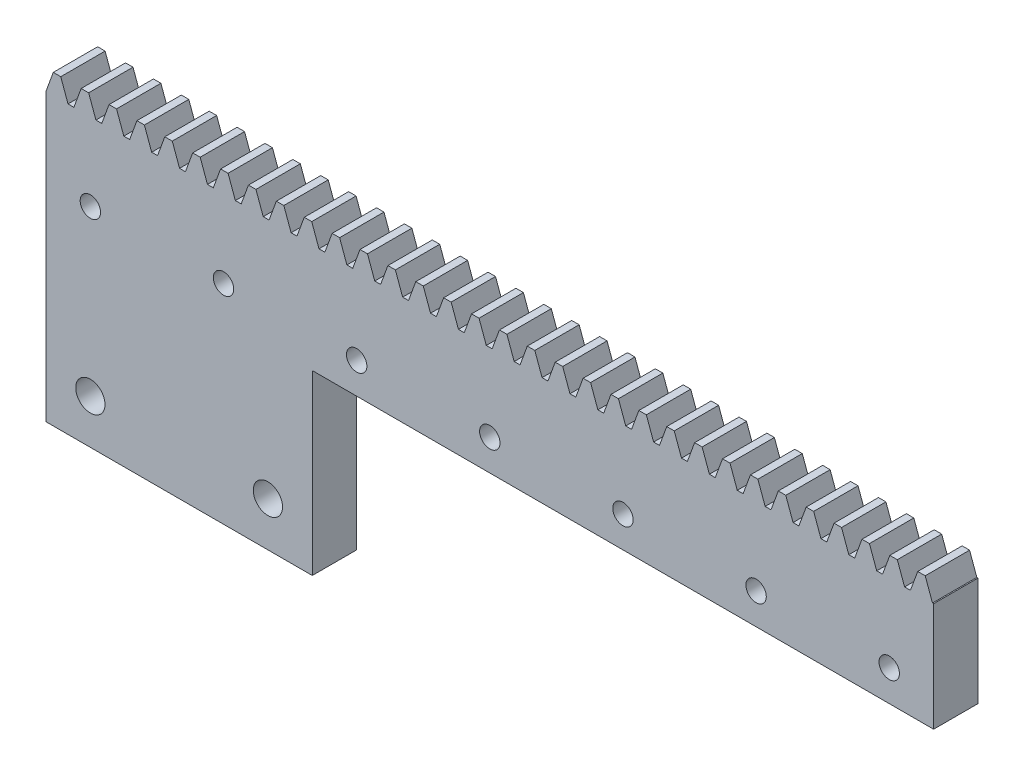
SolidWorks part; units mm, degrees
material "1.1193 (C45G)"
ref_plane "Front" through (0, 0, 0) normal (0, 0, 1) x (1, 0, 0)
ref_plane "Top" through (0, 0, 0) normal (0, 1, 0) x (1, 0, 0)
ref_plane "Right" through (0, 0, 0) normal (1, 0, 0) x (0, 0, -1)
sketch "Sketch1" plane through (0, 0, 0) normal (0, 0, 1) x (1, 0, 0)
  line L1 (0, 0) -> (106.8142, 0)
  line L2 (0, 0) -> (0, -8)
  line L3 (0, -8) -> (106.8142, -8)
  line L4 (106.8142, 0) -> (106.8142, -8)
  dimension "D1" = 8
  dimension "L" = 106.8142
extrude "Extrude1" add sketch "Sketch1" along normal blind 5
sketch "Sketch2" plane through (0, 0, 5) normal (0, 0, 1) x (1, 0, 0)
  line L0 (0, 0) -> (0.8189, 2.25)
  line L1 (0.8189, 2.25) -> (1.6618, 2.25)
  line L2 (1.6618, 2.25) -> (2.4807, 0)
  line L3 (106.8142, 0) -> (0, 0) construction
  line L4 (0, 0) -> (2.4807, 0)
  line L5 (0.455, 1.25) -> (2.0258, 1.25) construction
  dimension "alpha2" = 70
  dimension "alpha" = 110
  dimension "ha" = 1
  dimension "hf" = 1.25
  dimension "S" = 1.5708
extrude "Extrude2" add sketch "Sketch2" against normal up to surface (5 mm away) up to face at (53.4071, -4, 0)
pattern_linear "LPattern1" count 34 spacing 3.1416 along (1, 0, 0) of "Extrude2"
sketch "草图1" plane through (0, 0, 5) normal (0, 0, 1) x (1, 0, 0)
  line L0 (-1.6813, 1.25) -> (108.7223, 1.25) construction
  line L1 (3.1416, 0) -> (2.4807, 0) construction
  dimension "D1" = 1.25
sketch "草图2" plane through (0, -8, 0) normal (0, -1, 0) x (1, 0, 0)
  line L4 (0, 0) -> (106.8142, 0)
  line L5 (106.8142, 0) -> (106.8142, 5)
  line L6 (106.8142, 5) -> (0, 5)
  line L7 (0, 5) -> (0, 0)
  line L8 (0, 0) -> (106.8142, 0)
  line L9 (106.8142, 0) -> (106.8142, 5)
  line L10 (106.8142, 5) -> (0, 5)
  line L11 (0, 5) -> (0, 0)
  dimension "D1" = 0
extrude "凸台-拉伸1" add sketch "草图2" along normal blind 4.25
sketch "草图3" plane through (106.8142, 0, 0) normal (1, 0, 0) x (0, 0, -1)
  line L1 (-5, -12.25) -> (0, -12.25)
  line L2 (-5, -12.25) -> (-5, 5.5099)
  line L3 (-5, 5.5099) -> (0, 5.5099)
  line L4 (0, -12.25) -> (0, 5.5099)
extrude "切除-拉伸1" cut sketch "草图3" against normal offset from surface (6.8142 mm away) 100 up to face at (0, -6.125, 2.5)
sketch "草图4" plane through (0, 0, 5) normal (0, 0, 1) x (1, 0, 0)
  line L0 (0, -8.75) -> (100, -8.75) construction
  line L1 (0, 0) -> (0, -12.25) construction
  line L2 (100, -12.25) -> (100, 0) construction
  line L3 (100, -12.25) -> (0, -12.25) construction
  circle A0 centre (5, -8.75) radius 1.15
  circle A1 centre (20, -8.75) radius 1.15
  circle A2 centre (35, -8.75) radius 1.15
  circle A3 centre (50, -8.75) radius 1.15
  circle A4 centre (65, -8.75) radius 1.15
  circle A5 centre (80, -8.75) radius 1.15
  circle A6 centre (95, -8.75) radius 1.15
  dimension "D2" = 2.3
  dimension "D3" = 5
  dimension "D5" = 15
  dimension "D1" = 3.5
  dimension "D4" = 7
extrude "切除-拉伸2" cut sketch "草图4" against normal through all
sketch "草图5" plane through (0, 0, 5) normal (0, 0, 1) x (1, 0, 0)
  line L1 (0, -12.25) -> (30, -12.25)
  line L2 (0, -12.25) -> (0, -32.25)
  line L3 (0, -32.25) -> (30, -32.25)
  line L4 (30, -12.25) -> (30, -32.25)
  dimension "D1" = 20
  dimension "D2" = 30
extrude "凸台-拉伸2" add sketch "草图5" against normal up to surface (5 mm away) up to face at (6.15, -8.75, 0)
sketch "草图6" plane through (0, 0, 5) normal (0, 0, 1) x (1, 0, 0)
  line L0 (30, -27.25) -> (0, -27.25) construction
  line L1 (30, -32.25) -> (30, -12.25) construction
  line L2 (0, 0) -> (0, -32.25) construction
  line L3 (0, -32.25) -> (30, -32.25) construction
  circle A0 centre (25, -27.25) radius 1.65
  circle A1 centre (5, -27.25) radius 1.65
  dimension "D2" = 3.3
  dimension "D4" = 5
  dimension "D1" = 5
  dimension "D3" = 5
extrude "切除-拉伸3" cut sketch "草图6" against normal blind 13
